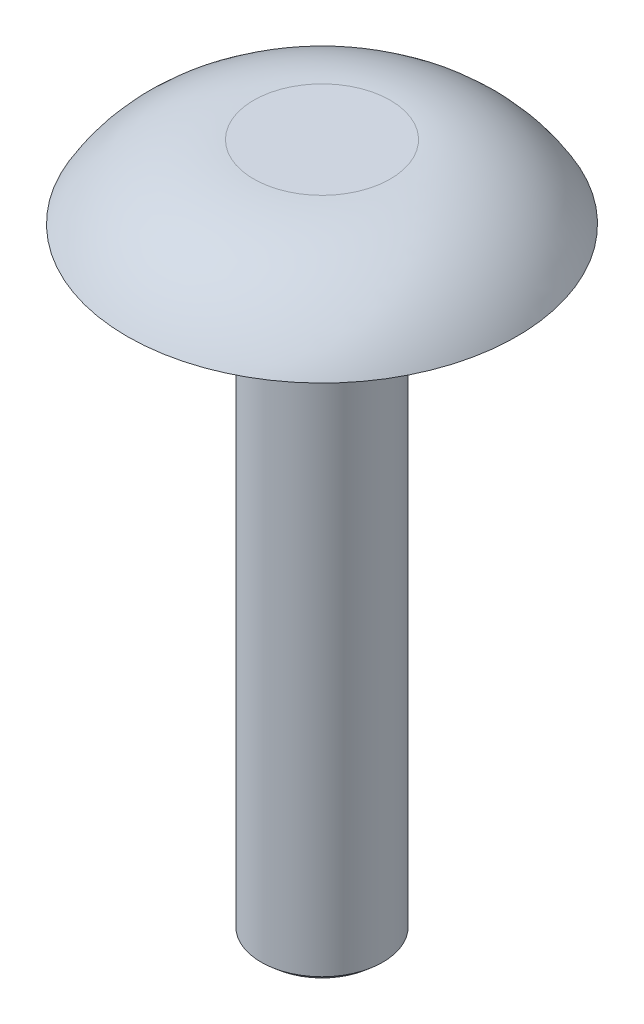
SolidWorks part; units mm, degrees
material "Nylon 6/10"
ref_plane "Face" through (0, 0, 0) normal (0, 0, 1) x (1, 0, 0)
ref_plane "Dessus" through (0, 0, 0) normal (0, 1, 0) x (1, 0, 0)
ref_plane "Droite" through (0, 0, 0) normal (1, 0, 0) x (0, 0, -1)
sketch "Esquisse1" plane through (0, 0, 0) normal (0, 0, 1) x (1, 0, 0)
  line L0 (0, 0) -> (0, 19.1967) construction
  line L1 (1.25, 13.5) -> (1.25, 0.5)
  line L2 (0, 0) -> (1.5234, 0) construction
  line L3 (1.4019, 14.5) -> (0, 14.5)
  line L4 (4, 13) -> (3, 13)
  line L5 (3, 13) -> (3, 13.5)
  line L6 (3, 13.5) -> (1.25, 13.5)
  line L7 (0, 14.5) -> (0, 0)
  arc A0 (1.25, 0.5) -> (0, 0) centre (0, 1.8125) cw
  arc A1 (1.4019, 14.5) -> (4, 13) centre (1.4019, 11.5) cw
  dimension "D6" = 3
  dimension "D1" = 2.5
  dimension "D2" = 0.5
  dimension "D3" = 13
  dimension "D4" = 14.5
  dimension "D5" = 0.5
  dimension "D7" = 8
  dimension "D8" = 1
revolve "Révolution1" add sketch "Esquisse1" angle 360 about L0
